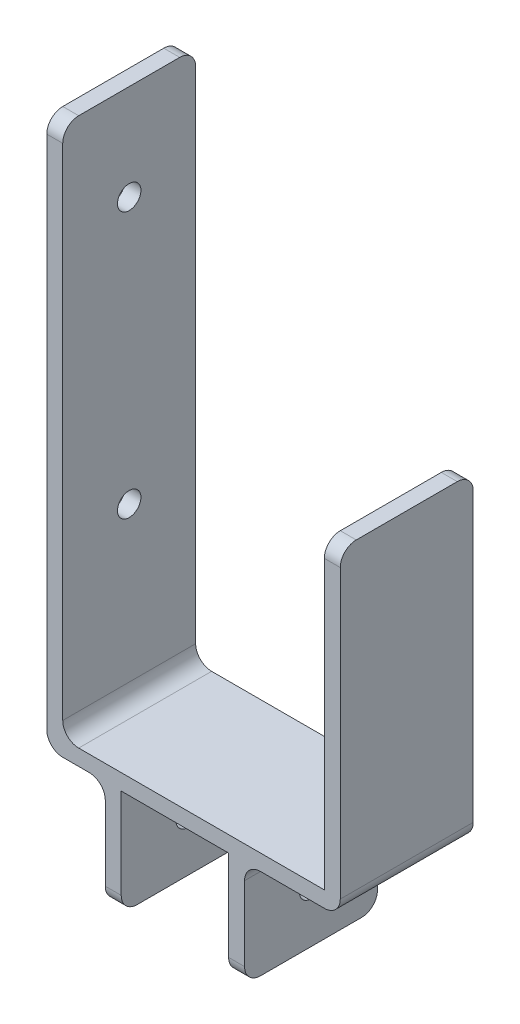
SolidWorks part; units mm, degrees
material "ABS"
ref_plane "Front Plane" through (0, 0, 0) normal (0, 0, 1) x (1, 0, 0)
ref_plane "Top Plane" through (0, 0, 0) normal (0, 1, 0) x (1, 0, 0)
ref_plane "Right Plane" through (0, 0, 0) normal (1, 0, 0) x (0, 0, -1)
sketch "Sketch1" plane through (0, 0, 0) normal (0, 0, 1) x (1, 0, 0)
  line L0 (-24.6, 0) -> (24.6, 0)
  line L1 (24.6, 0) -> (24.6, 57)
  line L2 (24.6, 57) -> (27.6, 57)
  line L3 (27.6, 57) -> (27.6, -3)
  line L4 (27.6, -3) -> (9.6, -3)
  line L5 (-27.6, -3) -> (-27.6, 100)
  line L6 (-27.6, 100) -> (-24.6, 100)
  line L7 (-24.6, 100) -> (-24.6, 0)
  line L8 (-16.6, -3) -> (-16.6, -23)
  line L9 (-16.6, -23) -> (-13.6, -23)
  line L10 (-13.6, -23) -> (-13.6, -3)
  line L11 (6.6, -3) -> (6.6, -23)
  line L12 (6.6, -23) -> (9.6, -23)
  line L13 (9.6, -23) -> (9.6, -3)
  line L14 (-16.6, -3) -> (-27.6, -3)
  line L15 (6.6, -3) -> (-13.6, -3)
  dimension "D2" = 49.2
  dimension "D3" = 3
  dimension "D4" = 57
  dimension "D5" = 100
  dimension "D6" = 3
  dimension "D7" = 3
  dimension "D8" = 20.2
  dimension "D9" = 3
  dimension "D10" = 20
  dimension "D11" = 11
extrude "Boss-Extrude1" add sketch "Sketch1" along normal blind 25
fillet "Fillet1" radius 3 13 edges at (8.1, -23, 25) (8.1, -23, 0) (-15.1, -23, 0) (-15.1, -23, 25) (-16.6, -3, 12.5) (9.6, -3, 12.5) (27.6, -3, 12.5) (-27.6, -3, 12.5) (-24.6, 0, 12.5) (26.1, 57, 0) (26.1, 57, 25) (-26.1, 100, 0) (-26.1, 100, 25)
sketch "Sketch2" plane through (-27.6, 0, 0) normal (-1, 0, 0) x (0, 0, 1)
  line L0 (12.5, -13) -> (12.5, -23) construction
  line L1 (22, -23) -> (3, -23) construction
  line L2 (12.5, 82) -> (12.5, 100) construction
  line L3 (22, 100) -> (3, 100) construction
  circle A0 centre (12.5, 82) radius 2.2
  circle A1 centre (12.5, 32) radius 2.2
  circle A2 centre (12.5, -13) radius 2.2
  dimension "D1" = 4.4
  dimension "D2" = 4.4
  dimension "D4" = 50
  dimension "D3" = 10
  dimension "D5" = 18
extrude "Cut-Extrude1" cut sketch "Sketch2" against normal blind 40
